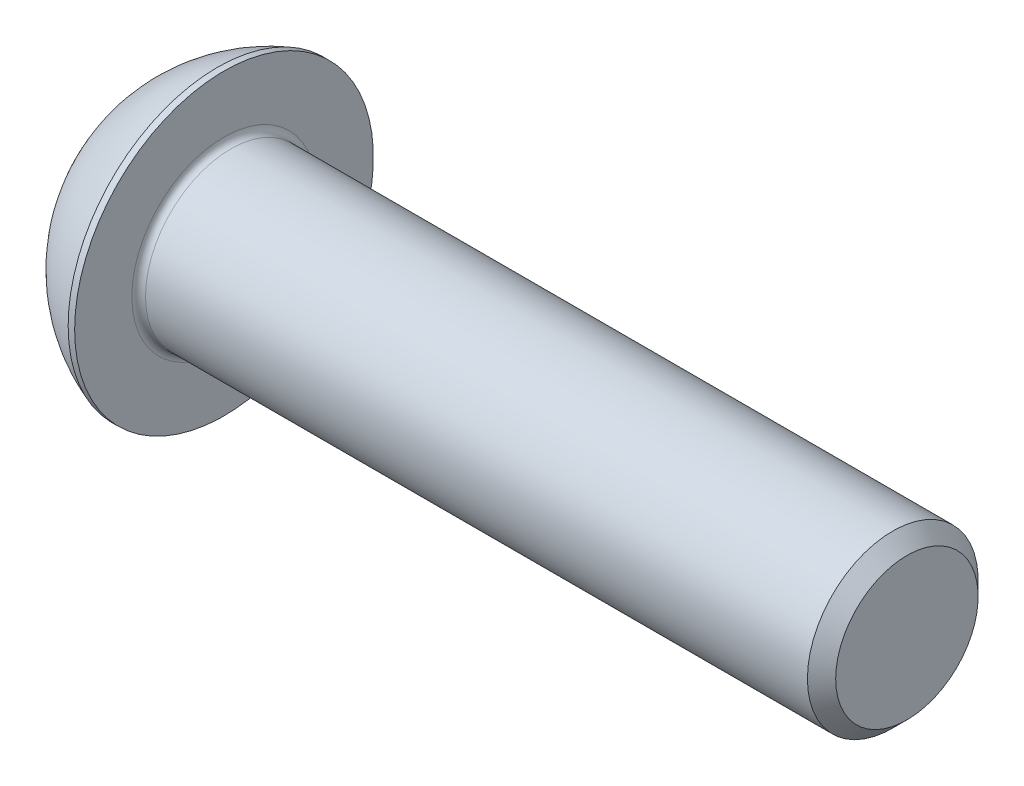
SolidWorks part; units mm, degrees
material "AISI 1035 Stahl"
ref_plane "Plane1" through (0, 0, 0) normal (0, 0, 1) x (1, 0, 0)
ref_plane "Plane2" through (0, 0, 0) normal (0, 1, 0) x (1, 0, 0)
ref_plane "Plane3" through (0, 0, 0) normal (1, 0, 0) x (0, 0, -1)
sketch "BodySke" plane through (0, 0, 0) normal (0, 0, 1) x (1, 0, 0)
  line L0 (45.5, 0) -> (45.5, 4.172)
  line L1 (44.672, 5) -> (5.5, 5)
  line L2 (5.5, 5) -> (5.5, 8.75)
  line L3 (5.5, 8.75) -> (5.12, 8.75)
  line L4 (0, 0) -> (101.6, 0) construction
  line L5 (5.5, -8.75) -> (5.12, -8.75) construction
  line L6 (55.6768, -5) -> (5.5, -5) construction
  line L7 (45.5, 0) -> (0, 0)
  line L8 (0, 4.375) -> (0, -4.375) construction
  line L9 (0, 0) -> (0, 4.375)
  line L10 (45.5, 4.172) -> (44.672, 5)
  line L11 (45.5, -4.172) -> (44.672, -5) construction
  line L12 (7, 9.525) -> (7, -5) construction
  line L13 (5.5, 9.525) -> (5.5, -5) construction
  arc A1 (0, 4.375) -> (5.12, 8.75) centre (8.1676, 0) cw
  dimension "Diameter" = 10
  dimension "Length" = 40
  dimension "Head_dia" = 17.5
  dimension "D1" = 8.75
  dimension "Head_ht" = 5.5
  dimension "Head_side_ht" = 0.38
  dimension "Minor_dia" = 8.344
  dimension "Body_ch_ang" = 45
  dimension "Advance" = 1.5
  dimension "Thread_nom" = 40
revolve "BaseBody" add sketch "BodySke" angle 360 about L4
cosmetic thread "ThreadCosmetic" [suppressed] parameters "Thread_length"=37, "Thread_minor"=8.344
fillet "Fillet1" radius 0.4 1 edges at (5.5, 0, 5)
sketch "Sketch2" plane through (0, 0, 0) normal (0, 0, 1) x (1, 0, 0)
  line L0 (0, 3) -> (3.12, 3)
  line L1 (3.12, 3) -> (4.8521, 0)
  line L3 (4.8521, 0) -> (0, 0)
  line L4 (0, 0) -> (0, 3)
  line L5 (0, -3) -> (3.12, -3) construction
  line L6 (0, 0) -> (47.625, 0) construction
  dimension "D2" = 60
  dimension "PreBroach_depth" = 3.12
  dimension "PreBroach_dia" = 6
revolve "PreBroach" cut sketch "Sketch2" angle 360 about L6
sketch "Sketch3" plane through (0, 0, 0) normal (1, 0, 0) x (0, 0, -1)
  line L0 (-3, -1.7321) -> (-3, 1.7321)
  line L1 (-3, 1.7321) -> (0, 3.4641)
  line L2 (0, 3.4641) -> (3, 1.7321)
  line L3 (3, 1.7321) -> (3, -1.7321)
  line L4 (3, -1.7321) -> (0, -3.4641)
  line L5 (0, -3.4641) -> (-3, -1.7321)
  dimension "Hex_size" = 6
  dimension "D3" = 6
  dimension "D1" = 3
  dimension "D2" = 3
extrude "Hex" cut sketch "Sketch3" along normal blind 3.12
sketch "ThdSchSke" plane through (0, 0, 0) normal (0, 0, 1) x (1, 0, 0)
  line L0 (8.5, -4.172) -> (7.9202, -5)
  line L1 (8.5, -4.172) -> (9.0798, -5)
  line L2 (9.0798, -5) -> (9.0798, -6.25)
  line L3 (-3.175, 0) -> (5.1513, 0) construction
  line L5 (9.0798, -6.25) -> (7.9202, -6.25)
  line L6 (7.9202, -6.25) -> (7.9202, -5)
  dimension "Diameter" = 10
  dimension "Thread_minor" = 8.344
  dimension "SideAngle" = 55
  dimension "VeeAngle" = 70
  dimension "Overcut" = 12.5
  dimension "Start" = 8.5
revolve "ThreadSchematic" [suppressed] cut sketch "ThdSchSke" angle 360 about L3
pattern_linear "ThdSchPat" [suppressed]
equation "\"D1@BodySke\" = \"Head_dia@BodySke\" * .5"
equation "\"Thread_minor@ThreadCosmetic\" = \"Minor_dia@BodySke\""
equation "\"D1@Sketch3\" = \"Hex_size@Sketch3\" / 2"
equation "\"D2@Sketch3\" = \"D1@Sketch3\""
equation "\"D3@Sketch3\" = \"Hex_size@Sketch3\""
equation "\"Thread_length@ThreadCosmetic\" = ((sgn( (\"Length@BodySke\" - \"Advance@BodySke\" * 2.0) - \"Thread_nom@BodySke\" )-1)*( (\"Length@BodySke\" - \"Advance@BodySke\" * 2.0) - \"Thread_nom@BodySke\" ))/-2+ \"Thread_nom@BodySke\""
equation "\"Thread_minor@ThdSchSke\" = \"Minor_dia@BodySke\""
equation "\"Diameter@ThdSchSke\" = \"Diameter@BodySke\""
equation "\"Overcut@ThdSchSke\" = \"Diameter@BodySke\" * 1.25"
equation "\"Start@ThdSchSke\" = \"Head_ht@BodySke\" + \"Length@BodySke\" - \"Thread_length@ThreadCosmetic\"  '---Non-countersunk---"
equation "\"Num_threads@ThdSchPat\" = int( \"Thread_length@ThreadCosmetic\" / \"Advance@BodySke\" + 0.999 )  + 1"
equation "\"Advance@ThdSchPat\" = \"Thread_length@ThreadCosmetic\" /  (\"Num_threads@ThdSchPat\" - 1) 'relax it"
equation "\"Num_threads@ThdSchPat\" = \"Num_threads@ThdSchPat\" - sgn( \"Num_threads@ThdSchPat\" - 1) '---chamfered tips only---"
